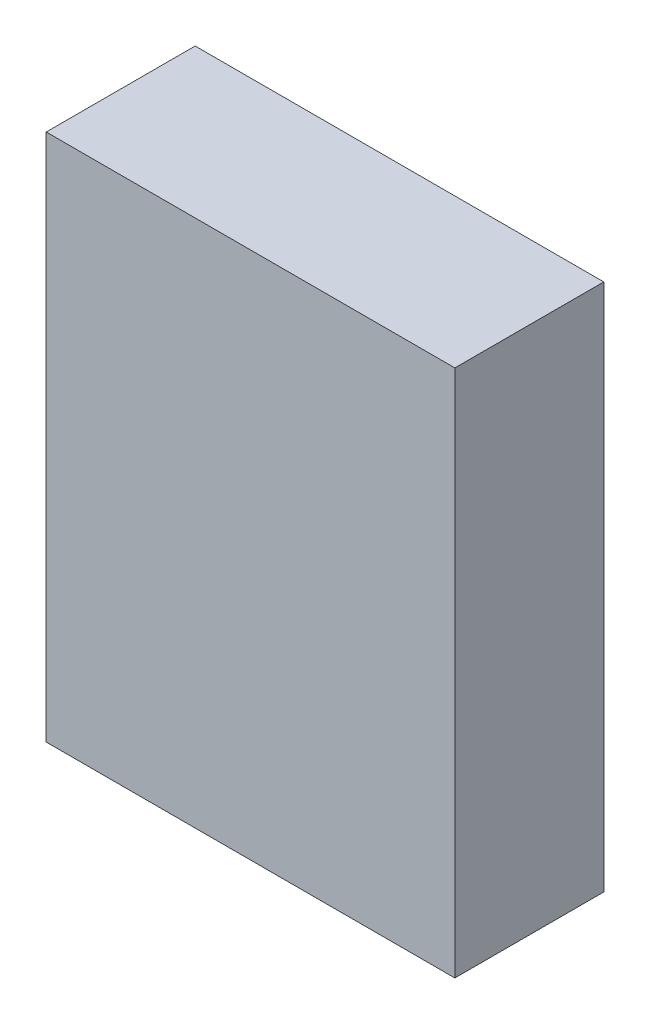
SolidWorks part; units mm, degrees
ref_plane "Front Plane" through (0, 0, 0) normal (0, 0, 1) x (1, 0, 0)
ref_plane "Top Plane" through (0, 0, 0) normal (0, 1, 0) x (1, 0, 0)
ref_plane "Right Plane" through (0, 0, 0) normal (1, 0, 0) x (0, 0, -1)
sketch "Sketch1" plane through (0, 0, 0) normal (0, 0, 1) x (1, 0, 0)
  line L1 (-770.8651, 173.48) -> (-742.7151, 173.48)
  line L2 (-770.8651, 173.48) -> (-770.8651, 137.08)
  line L3 (-770.8651, 137.08) -> (-742.7151, 137.08)
  line L4 (-742.7151, 173.48) -> (-742.7151, 137.08)
  dimension "D1" = 28.15
  dimension "D2" = 36.4
extrude "Boss-Extrude1" add sketch "Sketch1" along normal blind 10.26
sketch "Sketch2" plane through (0, 0, 10.26) normal (0, 0, 1) x (1, 0, 0)
  line L0 (-755.1516, 159.9521) -> (-753.1516, 159.9521)
  line L1 (-749.0876, 146.0991) -> (-749.0876, 167.1601)
  line L2 (-747.6876, 146.0991) -> (-747.6876, 167.1601)
  line L3 (-747.0556, 146.0991) -> (-747.0556, 167.1601)
  line L4 (-745.6556, 167.1601) -> (-747.0556, 167.1601)
  line L6 (-747.6876, 167.1601) -> (-749.0876, 167.1601)
  line L7 (-745.6556, 146.0991) -> (-747.0556, 146.0991)
  line L8 (-747.6876, 146.0991) -> (-749.0876, 146.0991)
  line L9 (-745.6556, 146.0991) -> (-745.6556, 167.1601)
  line L10 (-742.7151, 159.9521) -> (-745.5851, 159.9521)
  line L11 (-742.7151, 137.08) -> (-742.7151, 173.48) construction
  line L12 (-752.6275, 173.48) -> (-752.6275, 167.24)
  line L13 (-751.7516, 146.0991) -> (-753.1516, 146.0991)
  line L14 (-751.7516, 146.0991) -> (-751.7516, 167.1601)
  line L15 (-751.7516, 167.1601) -> (-753.1516, 167.1601)
  line L16 (-753.1516, 146.0991) -> (-753.1516, 167.1601)
  line L17 (-755.1516, 146.0991) -> (-760.9016, 146.0991)
  line L18 (-755.1516, 146.0991) -> (-755.1516, 167.1601)
  line L19 (-755.1516, 167.1601) -> (-760.9016, 167.1601)
  line L20 (-760.9016, 146.0991) -> (-760.9016, 167.1601)
  line L21 (-751.1196, 146.0991) -> (-751.1196, 167.1601)
  line L22 (-749.7196, 146.0991) -> (-749.7196, 167.1601)
  line L23 (-749.7196, 167.1601) -> (-751.1196, 167.1601)
  line L24 (-749.7196, 146.0991) -> (-751.1196, 146.0991)
  line L25 (-751.7516, 165.7235) -> (-751.1196, 165.7235)
  line L26 (-749.7196, 165.7235) -> (-749.0876, 165.7235)
  line L27 (-747.6876, 165.7235) -> (-747.0556, 165.7235)
  line L28 (-742.7151, 173.48) -> (-770.8651, 173.48) construction
  line L29 (-762.9982, 146.0991) -> (-764.3982, 146.0991)
  line L30 (-762.9982, 146.0991) -> (-762.9982, 167.1601)
  line L31 (-762.9982, 167.1601) -> (-764.3982, 167.1601)
  line L32 (-764.3982, 146.0991) -> (-764.3982, 167.1601)
  line L33 (-760.9016, 162.177) -> (-762.9016, 162.177)
  dimension "D2" = 2
  dimension "D3" = 2
  dimension "D4" = 5.75
  dimension "D5" = 2.87
  dimension "D6" = 6.24
  dimension "D7" = 0.632
  dimension "D8" = 2
  dimension "D12" = 2
